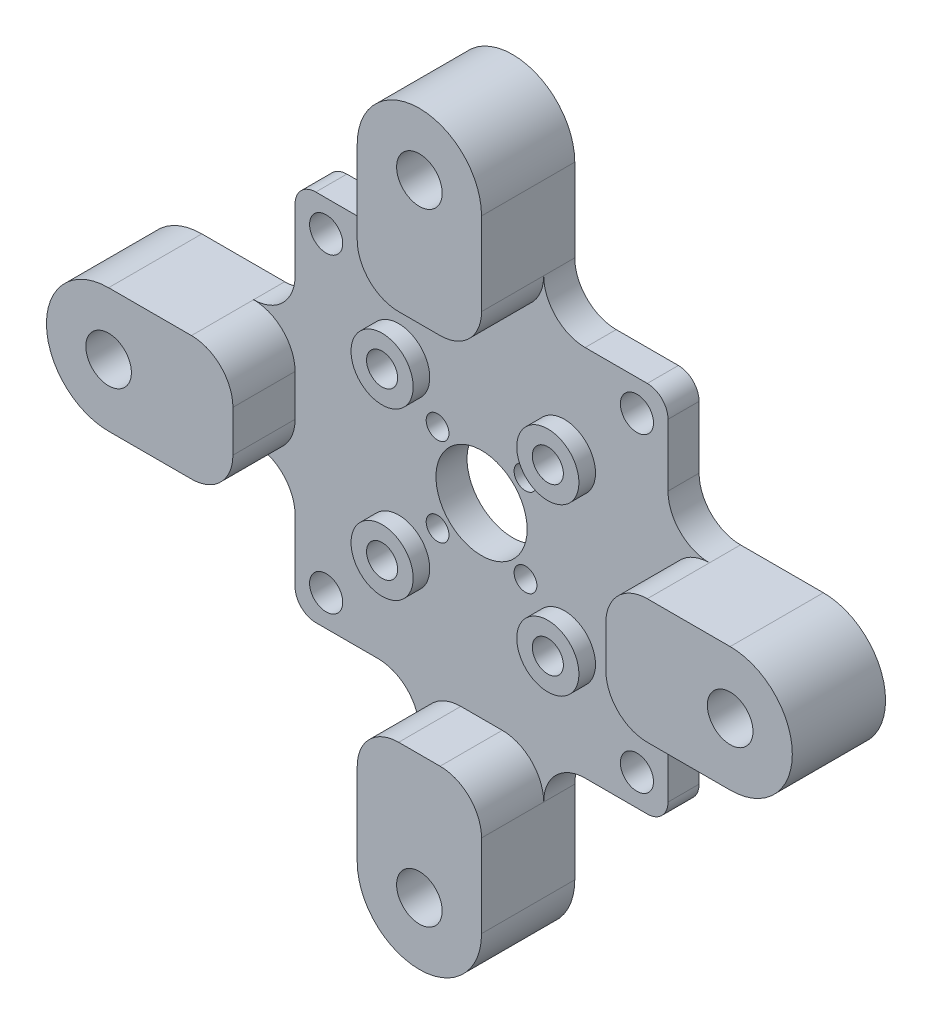
SolidWorks part; units mm, degrees
ref_plane "Plan de face" through (0, 0, 0) normal (0, 0, 1) x (1, 0, 0)
ref_plane "Plan de dessus" through (0, 0, 0) normal (0, 1, 0) x (1, 0, 0)
ref_plane "Plan de droite" through (0, 0, 0) normal (1, 0, 0) x (0, 0, -1)
sketch "Esquisse1" plane through (0, 0, 0) normal (0, 0, 1) x (1, 0, 0)
  line L0 (0, 6) -> (0, 0) construction
  line L1 (0, 0) -> (-4.2426, 4.2426) construction
  line L2 (0, 18) -> (0, 0) construction
  line L3 (18, -18) -> (-18, -18)
  line L4 (18, -18) -> (18, 18)
  line L5 (18, 18) -> (-18, 18)
  line L6 (-18, -18) -> (-18, 18)
  line L7 (18, -18) -> (-18, 18) construction
  line L8 (18, 18) -> (-18, -18) construction
  line L9 (0, 0) -> (18, 0) construction
  circle A0 centre (0, 0) radius 6 construction
  circle A1 centre (-4.2426, 4.2426) radius 1.1
  circle A2 centre (4.2426, 4.2426) radius 1.1
  circle A3 centre (4.2426, -4.2426) radius 1.1
  circle A4 centre (-4.2426, -4.2426) radius 1.1
  circle A5 centre (0, 0) radius 4.4
  circle A6 centre (-15, 15) radius 1.6
  circle A7 centre (0, 0) radius 15 construction
  circle A8 centre (15, 15) radius 1.6
  circle A9 centre (15, -15) radius 1.6
  circle A10 centre (-15, -15) radius 1.6
  point P14 (0, 0)
  dimension "D1" = 12
  dimension "D4" = 2.2
  dimension "D5" = 8.8
  dimension "D9" = 3.2
  dimension "D10" = 30
  dimension "D2" = 45
  dimension "D6" = 36
  dimension "D7" = 3
  dimension "D8" = 3
  dimension "D3" = 4
extrude "Boss.-Extru.1" add sketch "Esquisse1" along normal blind 3
sketch "Esquisse2" plane through (0, 0, 3) normal (0, 0, 1) x (1, 0, 0)
  line L1 (8, -8) -> (-8, -8) construction
  line L2 (8, -8) -> (8, 8) construction
  line L3 (8, 8) -> (-8, 8) construction
  line L4 (-8, -8) -> (-8, 8) construction
  line L5 (8, -8) -> (-8, 8) construction
  line L6 (8, 8) -> (-8, -8) construction
  circle A0 centre (-8, 8) radius 3
  circle A1 centre (8, 8) radius 3
  circle A2 centre (8, -8) radius 3
  circle A3 centre (-8, -8) radius 3
  point P0 (0, 0)
  dimension "D1" = 6
  dimension "D2" = 16
  dimension "D3" = 16
extrude "Boss.-Extru.2" add sketch "Esquisse2" along normal blind 1.6
sketch "Esquisse3" plane through (0, 0, 4.6) normal (0, 0, 1) x (1, 0, 0)
  line L0 (0, 17.8842) -> (0, 0) construction
  line L1 (0, 0) -> (17.8818, 0) construction
  circle A0 centre (-8, 8) radius 1.5
  circle A1 centre (-8, 8) radius 3 construction
  circle A2 centre (8, 8) radius 1.5
  circle A3 centre (8, -8) radius 1.5
  circle A4 centre (-8, -8) radius 1.5
  dimension "D1" = 3
extrude "Enlèv. mat.-Extru.1" cut sketch "Esquisse3" against normal through all
fillet "Congé1" radius 2 4 edges at (-18, 18, 1.5) (-18, -18, 1.5) (18, -18, 1.5) (18, 18, 1.5)
sketch "Esquisse4" plane through (0, 0, 3) normal (0, 0, 1) x (1, 0, 0)
  line L0 (-6, 30) -> (-6, 18)
  line L1 (16, 18) -> (-16, 18) construction
  line L2 (6, 30) -> (6, 18)
  line L3 (-6, 18) -> (6, 18)
  line L4 (30, 6) -> (18, 6)
  line L5 (30, -6) -> (18, -6)
  line L6 (18, 6) -> (18, -6)
  line L7 (6, -30) -> (6, -18)
  line L8 (-6, -30) -> (-6, -18)
  line L9 (6, -18) -> (-6, -18)
  line L10 (-30, -6) -> (-18, -6)
  line L11 (-30, 6) -> (-18, 6)
  line L12 (-18, -6) -> (-18, 6)
  circle A0 centre (0, 0) radius 30 construction
  circle A1 centre (0, 30) radius 2.2
  arc A2 (6, 30) -> (-6, 30) centre (0, 30) ccw
  circle A3 centre (30, 0) radius 2.2
  arc A4 (30, -6) -> (30, 6) centre (30, 0) ccw
  circle A5 centre (0, -30) radius 2.2
  arc A6 (-6, -30) -> (6, -30) centre (0, -30) ccw
  circle A7 centre (-30, 0) radius 2.2
  arc A8 (-30, 6) -> (-30, -6) centre (-30, 0) ccw
  point P31 (0, 0)
  dimension "D1" = 60
  dimension "D2" = 4.4
  dimension "D3" = 12
  dimension "D4" = 4
extrude "Boss.-Extru.3" add sketch "Esquisse4" along normal blind 6 and the other way blind 3
fillet "Congé2" radius 4 8 edges at (18, 6, 6) (18, -6, 6) (-6, -18, 6) (-6, 18, 6) (6, 18, 6) (6, -18, 6) (-18, 6, 6) (-18, -6, 6)
fillet "Congé3" radius 4 8 edges at (18, -6, 1.5) (18, 6, 1.5) (6, 18, 1.5) (-6, 18, 1.5) (-18, 6, 1.5) (-18, -6, 1.5) (-6, -18, 1.5) (6, -18, 1.5)
